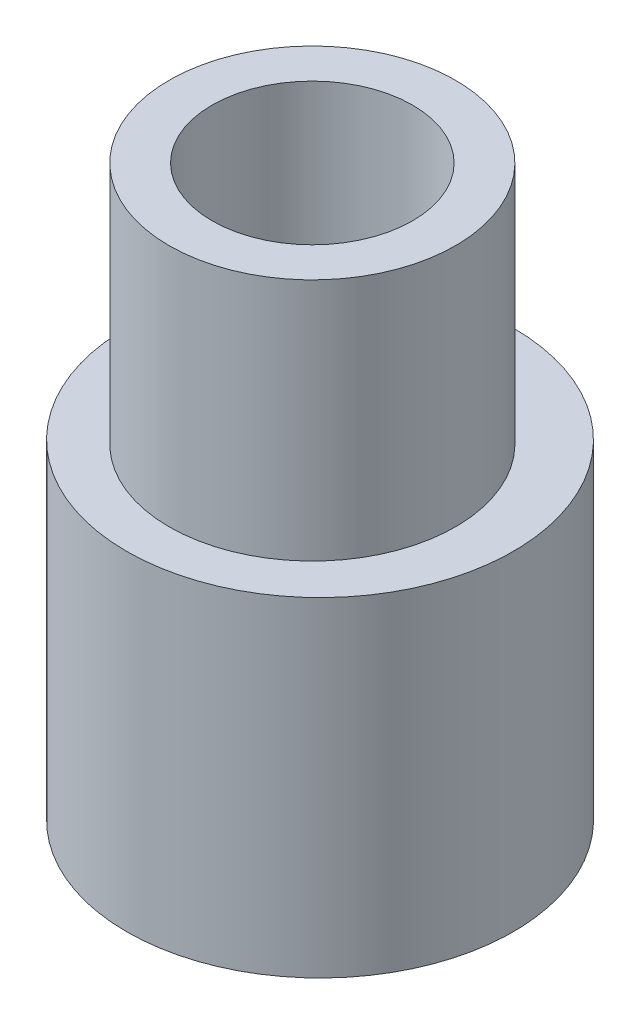
SolidWorks part; units mm, degrees
ref_plane "Front Plane" through (0, 0, 0) normal (0, 0, 1) x (1, 0, 0)
ref_plane "Top Plane" through (0, 0, 0) normal (0, 1, 0) x (1, 0, 0)
ref_plane "Right Plane" through (0, 0, 0) normal (1, 0, 0) x (0, 0, -1)
sketch "Sketch1" plane through (0, 0, 0) normal (0, 1, 0) x (1, 0, 0)
  circle A0 centre (0, 0) radius 2.54
  dimension "D1" = 5.08
extrude "Boss-Extrude1" add sketch "Sketch1" along normal blind 4.318
sketch "Sketch2" plane through (0, 4.318, 0) normal (0, 1, 0) x (1, 0, 0)
  circle A0 centre (0, 0) radius 1.778
  dimension "D1" = 3.556
extrude "Cut-Extrude1" cut sketch "Sketch2" against normal blind 3.048
sketch "Sketch4" plane through (0, 0, 0) normal (0, -1, 0) x (1, 0, 0)
  circle A0 centre (0, -0.1361) radius 3.429
extrude "Boss-Extrude2" add sketch "Sketch4" along normal blind 5.842
sketch "Sketch5" plane through (0, -5.842, 0) normal (0, -1, 0) x (1, 0, 0)
  circle A0 centre (0, 0) radius 2.794
  dimension "D1" = 5.588
extrude "Cut-Extrude2" cut sketch "Sketch5" against normal blind 4.826
